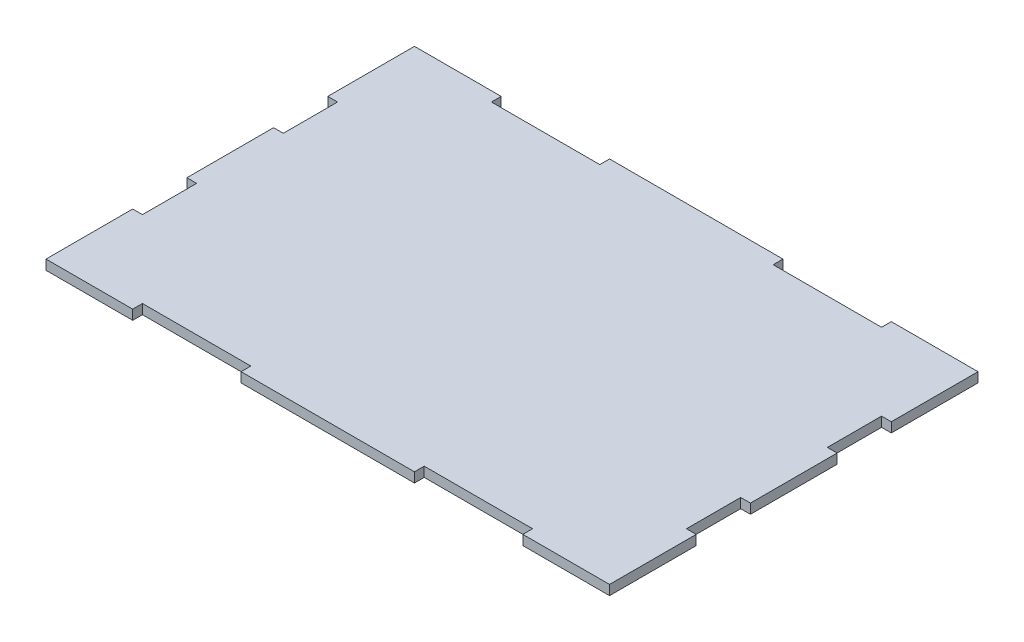
SolidWorks part; units mm, degrees
ref_plane "Front Plane" through (0, 0, 0) normal (0, 0, 1) x (1, 0, 0)
ref_plane "Top Plane" through (0, 0, 0) normal (0, 1, 0) x (1, 0, 0)
ref_plane "Right Plane" through (0, 0, 0) normal (1, 0, 0) x (0, 0, -1)
sketch "Sketch1" plane through (0, 0, 0) normal (0, 1, 0) x (1, 0, 0)
  line L0 (117.7019, 5.911) -> (117.7019, -164.089) construction
  line L1 (-12.2981, 5.911) -> (27.7019, 5.911)
  line L2 (-12.2981, 5.911) -> (-12.2981, -34.089)
  line L3 (-12.2981, -164.089) -> (27.7019, -164.089)
  line L4 (247.7019, 5.911) -> (247.7019, -34.089)
  line L6 (27.7019, 5.911) -> (27.7019, 1.411)
  line L7 (27.7019, 1.411) -> (77.7019, 1.411)
  line L8 (77.7019, 5.911) -> (77.7019, 1.411)
  line L9 (-12.2981, -79.089) -> (247.7019, -79.089) construction
  line L10 (-12.2981, -99.089) -> (-7.7981, -99.089)
  line L11 (-12.2981, -34.089) -> (-7.7981, -34.089)
  line L13 (-12.2981, -59.089) -> (-7.7981, -59.089)
  line L14 (-7.7981, -34.089) -> (-7.7981, -59.089)
  line L15 (-7.7981, -124.089) -> (-7.7981, -99.089)
  line L16 (-12.2981, -124.089) -> (-7.7981, -124.089)
  line L18 (27.7019, -159.589) -> (77.7019, -159.589)
  line L19 (77.7019, -164.089) -> (77.7019, -159.589)
  line L21 (27.7019, -164.089) -> (27.7019, -159.589)
  line L22 (207.7019, 1.411) -> (157.7019, 1.411)
  line L23 (157.7019, 5.911) -> (157.7019, 1.411)
  line L25 (207.7019, 5.911) -> (207.7019, 1.411)
  line L26 (207.7019, -164.089) -> (207.7019, -159.589)
  line L28 (157.7019, -164.089) -> (157.7019, -159.589)
  line L29 (207.7019, -159.589) -> (157.7019, -159.589)
  line L30 (247.7019, -59.089) -> (243.2019, -59.089)
  line L31 (243.2019, -34.089) -> (243.2019, -59.089)
  line L32 (247.7019, -34.089) -> (243.2019, -34.089)
  line L35 (247.7019, -124.089) -> (243.2019, -124.089)
  line L36 (243.2019, -124.089) -> (243.2019, -99.089)
  line L37 (247.7019, -99.089) -> (243.2019, -99.089)
  line L38 (-12.2981, -59.089) -> (-12.2981, -99.089)
  line L39 (77.7019, 5.911) -> (157.7019, 5.911)
  line L40 (207.7019, 5.911) -> (247.7019, 5.911)
  line L41 (247.7019, -59.089) -> (247.7019, -99.089)
  line L42 (247.7019, -124.089) -> (247.7019, -164.089)
  line L43 (207.7019, -164.089) -> (247.7019, -164.089)
  line L44 (77.7019, -164.089) -> (157.7019, -164.089)
  line L45 (-12.2981, -124.089) -> (-12.2981, -164.089)
  point P40 (0, 0)
  dimension "D1" = 260
  dimension "D2" = 170
  dimension "D3" = 50
  dimension "D4" = 40
  dimension "D5" = 25
  dimension "D6" = 40
  dimension "D7" = 4.5
  dimension "D8" = 4.5
extrude "Boss-Extrude1" add sketch "Sketch1" along normal blind 4.5
